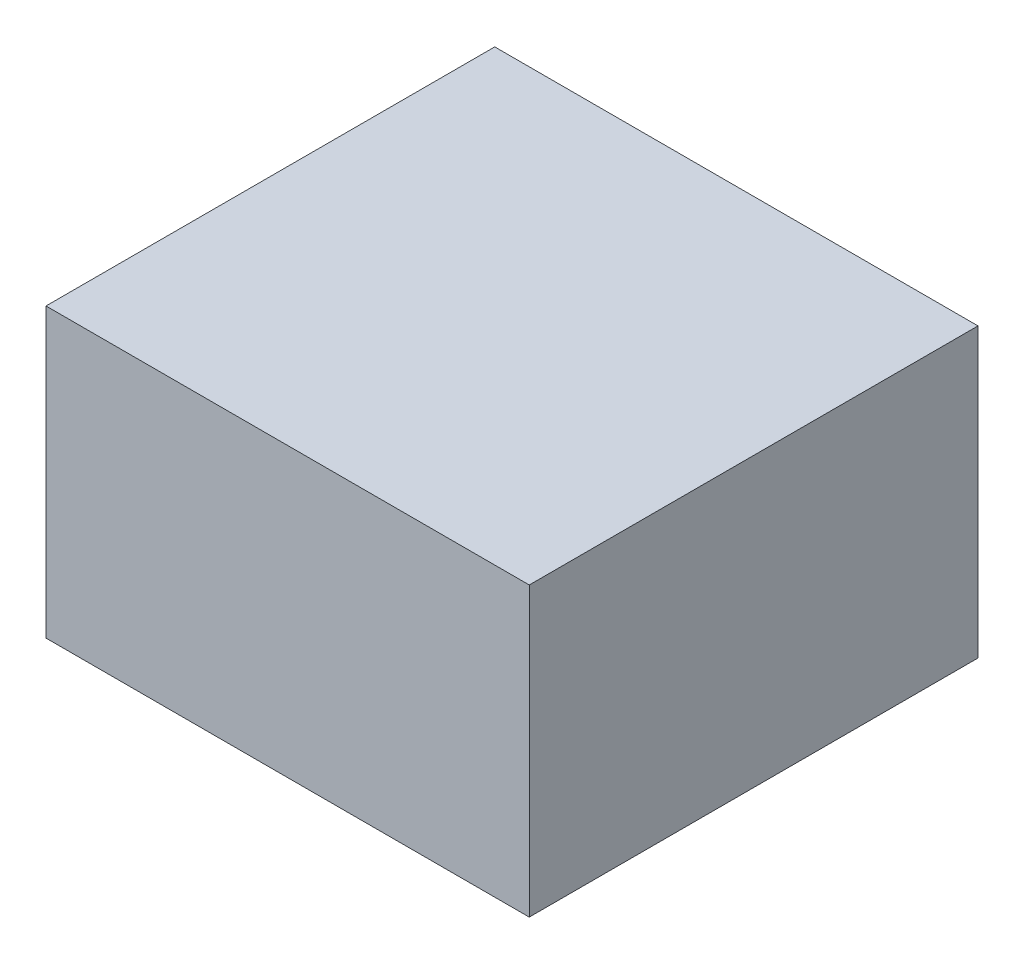
SolidWorks part; units mm, degrees
ref_plane "Plan de face" through (0, 0, 0) normal (0, 0, 1) x (1, 0, 0)
ref_plane "Plan de dessus" through (0, 0, 0) normal (0, 1, 0) x (1, 0, 0)
ref_plane "Plan de droite" through (0, 0, 0) normal (1, 0, 0) x (0, 0, -1)
sketch "Esquisse1" plane through (0, 0, 0) normal (0, 0, 1) x (1, 0, 0)
  line L1 (21, -12.5) -> (-21, -12.5)
  line L2 (21, -12.5) -> (21, 12.5)
  line L3 (21, 12.5) -> (-21, 12.5)
  line L4 (-21, -12.5) -> (-21, 12.5)
  line L5 (21, -12.5) -> (-21, 12.5) construction
  line L6 (21, 12.5) -> (-21, -12.5) construction
  point P0 (0, 0)
  dimension "D1" = 42
  dimension "D2" = 25
extrude "Boss.-Extru.1" add sketch "Esquisse1" along normal blind 39
sketch "Esquisse2" plane through (0, 0, 0) normal (0, 0, -1) x (-1, 0, 0)
  line L0 (21, 12.5) -> (21, -12.5) construction
  line L1 (6, -1.7878) -> (16, -1.7878)
  line L2 (6, -1.7878) -> (6, 1.2122)
  line L3 (6, 1.2122) -> (16, 1.2122)
  line L4 (16, -1.7878) -> (16, 1.2122)
  line L5 (6, -1.7878) -> (16, 1.2122) construction
  line L6 (6, 1.2122) -> (16, -1.7878) construction
  point P0 (11, -0.2878)
  dimension "D1" = 5
  dimension "D2" = 10
  dimension "D3" = 3
extrude "Enlèv. mat.-Extru.1" cut sketch "Esquisse2" against normal blind 10
sketch "Esquisse3" plane through (-16, 0, 0) normal (1, 0, 0) x (0, 0, -1)
  line L0 (-10, -1.7878) -> (0, -1.7878) construction
  line L1 (-10, 1.2122) -> (-6, 1.2122)
  line L2 (-10, 1.2122) -> (-10, -1.7878)
  line L3 (-10, -1.7878) -> (-6, -1.7878)
  line L4 (-6, 1.2122) -> (-6, -1.7878)
  dimension "D1" = 4
extrude "Enlèv. mat.-Extru.2" cut sketch "Esquisse3" against normal blind 10
